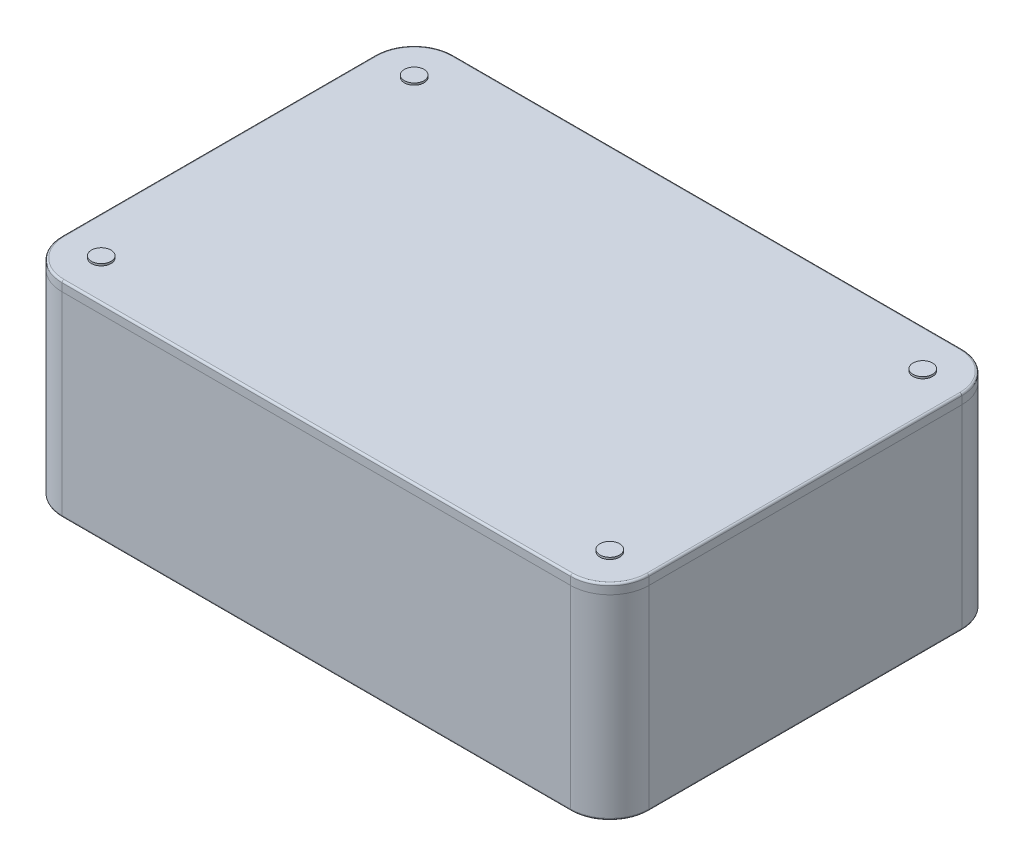
SolidWorks part; units mm, degrees
ref_plane "Alzado" through (0, 0, 0) normal (0, 0, 1) x (1, 0, 0)
ref_plane "Planta" through (0, 0, 0) normal (0, 1, 0) x (1, 0, 0)
ref_plane "Vista lateral" through (0, 0, 0) normal (1, 0, 0) x (0, 0, -1)
sketch "Croquis1" plane through (0, 0, 0) normal (0, 1, 0) x (1, 0, 0)
  line L1 (150, -100) -> (-150, -100)
  line L2 (150, -100) -> (150, 100)
  line L3 (150, 100) -> (-150, 100)
  line L4 (-150, -100) -> (-150, 100)
  line L5 (150, -100) -> (-150, 100) construction
  line L6 (150, 100) -> (-150, -100) construction
  point P0 (0, 0)
  dimension "D1" = 200
  dimension "D2" = 300
extrude "Extruir1" add sketch "Croquis1" along normal blind 100
fillet "Redondeo1" radius 20 4 edges at (-150, 50, -100) (150, 50, -100) (150, 50, 100) (-150, 50, 100)
shell "Vaciado1" thickness 4
sketch "Croquis2" plane through (0, 100, 0) normal (0, 1, 0) x (1, 0, 0)
  line L4 (130, 100) -> (-130, 100)
  line L5 (-150, 80) -> (-150, -80)
  line L6 (-130, -100) -> (130, -100)
  line L7 (150, -80) -> (150, 80)
  line L8 (130, 100) -> (-130, 100)
  line L9 (-150, 80) -> (-150, -80)
  line L10 (-130, -100) -> (130, -100)
  line L11 (150, -80) -> (150, 80)
  arc A4 (-130, 100) -> (-150, 80) centre (-130, 80) ccw
  arc A5 (-150, -80) -> (-130, -100) centre (-130, -80) ccw
  arc A6 (130, -100) -> (150, -80) centre (130, -80) ccw
  arc A7 (150, 80) -> (130, 100) centre (130, 80) ccw
  arc A8 (-130, 100) -> (-150, 80) centre (-130, 80) ccw
  arc A9 (-150, -80) -> (-130, -100) centre (-130, -80) ccw
  arc A10 (130, -100) -> (150, -80) centre (130, -80) ccw
  arc A11 (150, 80) -> (130, 100) centre (130, 80) ccw
  dimension "D1" = 0
extrude "Extruir2" add sketch "Croquis2" along normal blind 5 separate body
fillet "Redondeo2" radius 1 8 edges at (150, 105, 0) (144.1421, 105, 94.1421) (0, 105, 100) (-144.1421, 105, 94.1421) (-150, 105, 0) (-144.1421, 105, -94.1421) (0, 105, -100) (144.1421, 105, -94.1421)
sketch "Croquis3" plane through (0, 105, 0) normal (0, 1, 0) x (1, 0, 0)
  line L0 (0, 0) -> (0, 99) construction
  line L1 (130, 99) -> (-130, 99) construction
  line L2 (0, 0) -> (149, 0) construction
  line L3 (149, -80) -> (149, 80) construction
  circle A0 centre (-130, 80) radius 5
  arc A1 (-130, 100) -> (-150, 80) centre (-130, 80) ccw construction
  circle A2 centre (130, 80) radius 5
  circle A3 centre (130, -80) radius 5
  circle A4 centre (-130, -80) radius 5
  dimension "D1" = 10
extrude "Extruir3" add sketch "Croquis3" along normal blind 1 separate body
sketch "Croquis4" plane through (0, 106, 0) normal (0, 1, 0) x (1, 0, 0)
  circle A0 centre (-130, 80) radius 2.5
  circle A1 centre (130, 80) radius 2.5
  circle A2 centre (130, -80) radius 2.5
  circle A3 centre (-130, -80) radius 2.5
  dimension "D1" = 5
extrude "Extruir4" add sketch "Croquis4" against normal up to surface (102 mm away) up to face at (0, 4, 0)
sketch "Croquis5" plane through (0, 4, 0) normal (0, 1, 0) x (1, 0, 0)
  line L0 (-146, 26) -> (146, 26) construction
  line L1 (-146, 80) -> (-146, -80) construction
  line L2 (146, -80) -> (146, 80) construction
  line L3 (130, 96) -> (-130, 96) construction
  line L4 (-146, -26) -> (146, -26) construction
  line L5 (146, -80) -> (146, 80) construction
  line L7 (-101, 26) -> (-101, -26) construction
  line L8 (-21, 26) -> (-21, -26) construction
  line L9 (49, 26) -> (49, -26) construction
  line L10 (-130, -96) -> (130, -96) construction
  line L11 (49, 0) -> (109, 0) construction
  circle A0 centre (-101, 26) radius 4
  circle A1 centre (-101, -26) radius 4
  circle A2 centre (-21, 26) radius 4
  circle A3 centre (-21, -26) radius 4
  circle A4 centre (49, 26) radius 4
  circle A5 centre (49, -26) radius 4
  circle A6 centre (109, 0) radius 4
  point P18 (-146, 0)
  dimension "D4" = 8
  dimension "D1" = 70
  dimension "D2" = 70
  dimension "D3" = 45
  dimension "D5" = 80
  dimension "D6" = 70
  dimension "D7" = 60
extrude "Cortar-Extruir1" cut sketch "Croquis5" against normal blind 10
fillet "Redondeo3" radius 1 8 edges at (-144.1421, 0, 94.1421) (0, 0, 100) (144.1421, 0, 94.1421) (150, 0, 0) (144.1421, 0, -94.1421) (0, 0, -100) (-144.1421, 0, -94.1421) (-150, 0, 0)
sketch "Croquis6" plane through (0, 0, -100) normal (0, 0, -1) x (-1, 0, 0)
  line L0 (130, 50.5) -> (-130, 50.5) construction
  line L1 (130, 1) -> (130, 100) construction
  line L2 (-130, 100) -> (-130, 1) construction
  circle A0 centre (105, 50.5) radius 5
  circle A1 centre (-45, 50.5) radius 5
  circle A2 centre (-105, 50.5) radius 3
  dimension "D1" = 10
  dimension "D2" = 25
  dimension "D3" = 150
  dimension "D4" = 6
  dimension "D5" = 60
extrude "Extruir5" cut sketch "Croquis6" against normal blind 10
